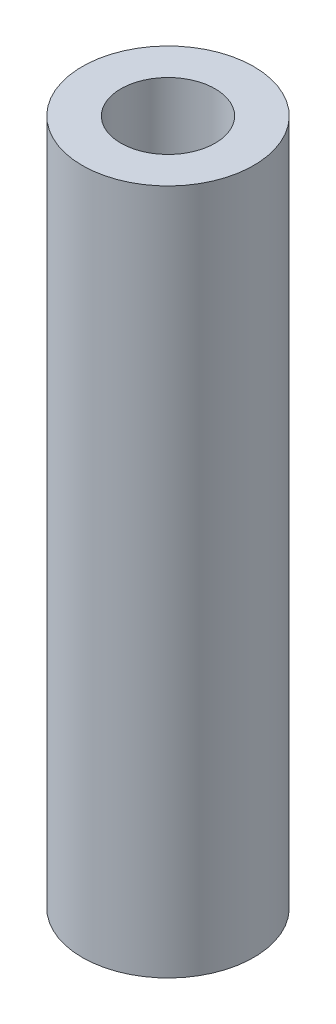
SolidWorks part; units mm, degrees
ref_plane "Ebene vorne" through (0, 0, 0) normal (0, 0, 1) x (1, 0, 0)
ref_plane "Ebene oben" through (0, 0, 0) normal (0, 1, 0) x (1, 0, 0)
ref_plane "Ebene rechts" through (0, 0, 0) normal (1, 0, 0) x (0, 0, -1)
sketch "Skizze1" plane through (0, 0, 0) normal (0, 1, 0) x (1, 0, 0)
  circle A0 centre (0, 0) radius 2.75
  circle A1 centre (0, 0) radius 5
  dimension "D1" = 5.5
  dimension "D2" = 10
extrude "Aufsatz-Linear austragen1" add sketch "Skizze1" along normal blind 40
